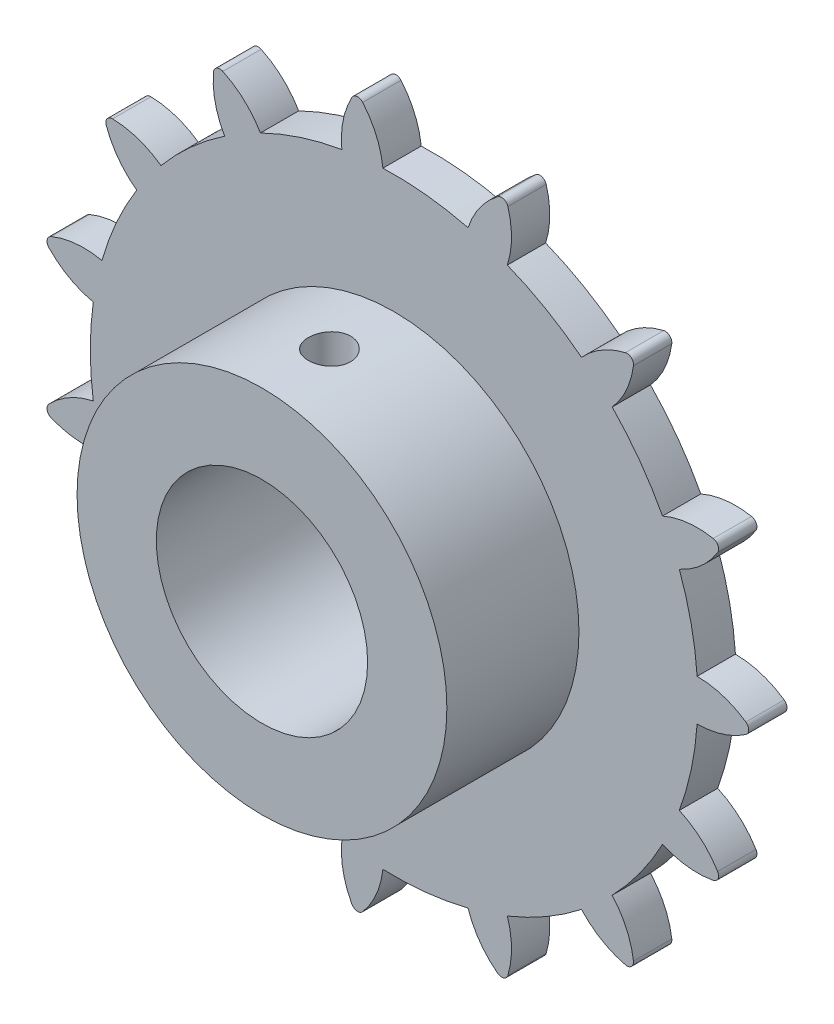
SolidWorks part; units mm, degrees
ref_plane "Front Plane" through (0, 0, 0) normal (0, 0, 1) x (1, 0, 0)
ref_plane "Top Plane" through (0, 0, 0) normal (0, 1, 0) x (1, 0, 0)
ref_plane "Right Plane" through (0, 0, 0) normal (1, 0, 0) x (0, 0, -1)
sketch "Sketch1" plane through (0, 0, 0) normal (0, 0, 1) x (1, 0, 0)
  circle A0 centre (0, 0) radius 11.5
extrude "Boss-Extrude1" add sketch "Sketch1" along normal blind 1.45
sketch "Sketch2" plane through (0, 0, 1.45) normal (0, 0, 1) x (1, 0, 0)
  line L3 (11.4664, -0.7818) -> (11.4664, 0.7818)
  arc A0 (11.4664, 0.7818) -> (13.3176, 0.2059) centre (11.4664, -2.4818) cw
  arc A1 (11.4664, -0.7818) -> (13.3176, -0.2059) centre (11.4664, 2.4818) ccw
  arc A2 (13.3176, 0.2059) -> (13.3176, -0.2059) centre (13.1758, 0) cw
  dimension "D1" = 0.25
extrude "Boss-Extrude2" add sketch "Sketch2" against normal blind 1.45
pattern_circular "CirPattern2" count 15 over 360 about axis through (0, 0, 0) along (0, 0, 1) of "Boss-Extrude2"
sketch "Sketch4" plane through (0, 0, 1.45) normal (0, 0, 1) x (1, 0, 0)
  circle A0 centre (0, 0) radius 4
extrude "Cut-Extrude1" cut sketch "Sketch4" against normal blind 1.45
sketch "Sketch5" plane through (0, 0, 1.45) normal (0, 0, 1) x (1, 0, 0)
  circle A0 centre (0, 0) radius 4
  circle A1 centre (0, 0) radius 7
extrude "Boss-Extrude3" add sketch "Sketch5" along normal blind 5
hole_wizard "M2x0.4 Tapped Hole3" positions "3DSketch6" profile "Sketch10" tap size "M2x0.4" standard "Ansi Metric"
sketch3d "3DSketch6"
  point P0 (-0.022, 7, 3.8749)
sketch "Sketch10" plane through (-0.022, 7, 3.8749) normal (0, 0, 1) x (-1, -0.0031, 0)
  line L0 (0, 0) -> (0, 5.6807)
  line L1 (0, 5.6807) -> (0.8, 5.2)
  line L2 (0.8, 5.2) -> (0.8, 0)
  line L5 (0.8, 0) -> (0, 0)
  line L10 (0, 5.6807) -> (-0.8, 5.2) construction
  line L11 (0, -6.35) -> (0, 107.95) construction
  dimension "Tap Drill Dia." = 1.6
  dimension "Tap Drill Depth" = 5.2
  dimension "Drill Angle" = 118
